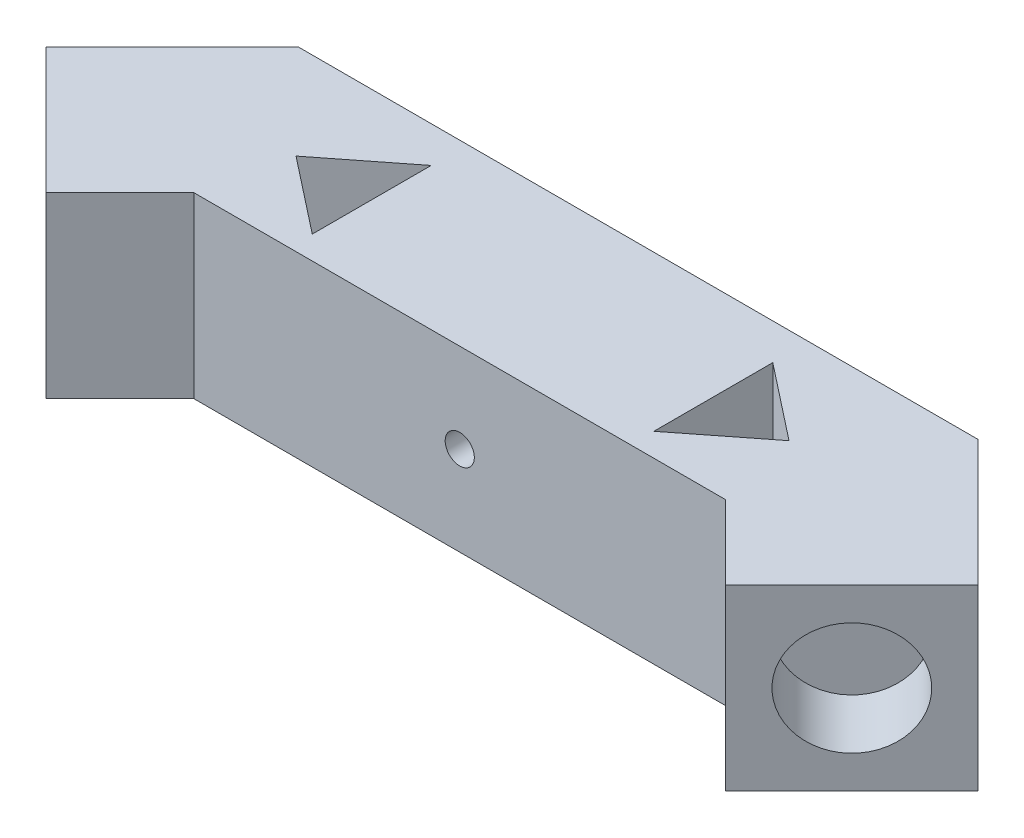
SolidWorks part; units mm, degrees
ref_plane "Front Plane" through (0, 0, 0) normal (0, 0, 1) x (1, 0, 0)
ref_plane "Top Plane" through (0, 0, 0) normal (0, 1, 0) x (1, 0, 0)
ref_plane "Right Plane" through (0, 0, 0) normal (1, 0, 0) x (0, 0, -1)
sketch "Sketch1" plane through (0, 0, 0) normal (0, 1, 0) x (1, 0, 0)
  line L1 (0, 0) -> (113.5797, 0)
  line L3 (-15.7815, 38.1) -> (129.3612, 38.1)
  line L5 (0, 0) -> (-15.7815, -15.7815)
  line L6 (-42.7223, 11.1592) -> (-15.7815, -15.7815)
  line L7 (56.7898, 38.1) -> (56.7898, 0) construction
  line L8 (113.5797, 0) -> (129.3612, -15.7815)
  line L9 (156.302, 11.1592) -> (129.3612, -15.7815)
  line L10 (129.3612, 38.1) -> (156.302, 11.1592)
  line L11 (-15.7815, 38.1) -> (-42.7223, 11.1592)
  dimension "D1" = 38.1
  dimension "D2" = 135
  dimension "D3" = 38.1
  dimension "D4" = 90
  dimension "D5" = 38.1
  dimension "D6" = 90
  dimension "D7" = 38.1
  dimension "D8" = 38.1
  dimension "D9" = 90
  dimension "D10" = 90
  dimension "D11" = 38.1
  dimension "D12" = 22.3185
  dimension "D13" = 56.7898
extrude "Boss-Extrude1" add sketch "Sketch1" along normal blind 38.1
sketch "Sketch2" plane through (-15.7815, 0, 15.7815) normal (-0.7071, 0, 0.7071) x (0.7071, 0, 0.7071)
  line L0 (-38.1, 38.1) -> (0, 0) construction
  line L1 (-38.1, 0) -> (0, 38.1) construction
  circle A0 centre (-19.05, 19.05) radius 12.065
  dimension "D1" = 24.13
extrude "Cut-Extrude1" cut sketch "Sketch2" against normal blind 15.24
sketch "Sketch3" plane through (72.5714, 0, 72.5714) normal (0.7071, 0, 0.7071) x (0.7071, 0, -0.7071)
  line L0 (80.313, 38.1) -> (118.413, 0) construction
  line L1 (80.313, 0) -> (118.413, 38.1) construction
  circle A0 centre (99.363, 19.05) radius 12.065
  point P11 (99.363, 19.05)
  dimension "D1" = 24.13
extrude "Cut-Extrude2" cut sketch "Sketch3" against normal blind 15.24
sketch "Sketch5" plane through (0, 38.1, 0) normal (0, 1, 0) x (1, 0, 0)
  line L0 (56.7898, 38.1) -> (56.7898, 0) construction
  line L1 (129.3612, 38.1) -> (-15.7815, 38.1) construction
  line L2 (0, 0) -> (113.5797, 0) construction
  line L3 (2.7565, 17.6768) -> (45.3845, 17.6768) construction
  line L4 (4.1516, 17.6768) -> (20.32, 30.3768)
  line L5 (20.32, 30.3768) -> (20.32, 4.9768)
  line L6 (20.32, 4.9768) -> (4.1516, 17.6768)
  line L7 (32.8523, 38.1) -> (32.8523, 0) construction
  line L13 (93.2597, 30.3768) -> (93.2597, 4.9768)
  line L14 (109.4281, 17.6768) -> (93.2597, 30.3768)
  line L15 (93.2597, 4.9768) -> (109.4281, 17.6768)
  line L19 (68.1951, 17.6768) -> (110.8231, 17.6768) construction
  dimension "D1" = 25.4
  dimension "D2" = 32.8523
  dimension "D3" = 38.149
  dimension "D4" = 20.32
  dimension "D5" = 42.628
  dimension "D6" = 42.628
  dimension "D7" = 17.6768
extrude "Cut-Extrude3" cut sketch "Sketch5" against normal blind 38.1
sketch "Sketch6" plane through (0, 0, -38.1) normal (0, 0, -1) x (-1, 0, 0)
  line L0 (-56.7898, 38.1) -> (-56.7898, 0) construction
  line L1 (-129.3612, 38.1) -> (15.7815, 38.1) construction
  line L2 (-129.3612, 0) -> (15.7815, 0) construction
  line L3 (-129.3612, 19.05) -> (15.7815, 19.05) construction
  line L4 (-129.3612, 38.1) -> (-129.3612, 0) construction
  line L5 (15.7815, 38.1) -> (15.7815, 0) construction
  circle A0 centre (-56.7898, 19.05) radius 3.1115
  dimension "D1" = 6.223
extrude "Cut-Extrude4" cut sketch "Sketch6" against normal blind 46.482
